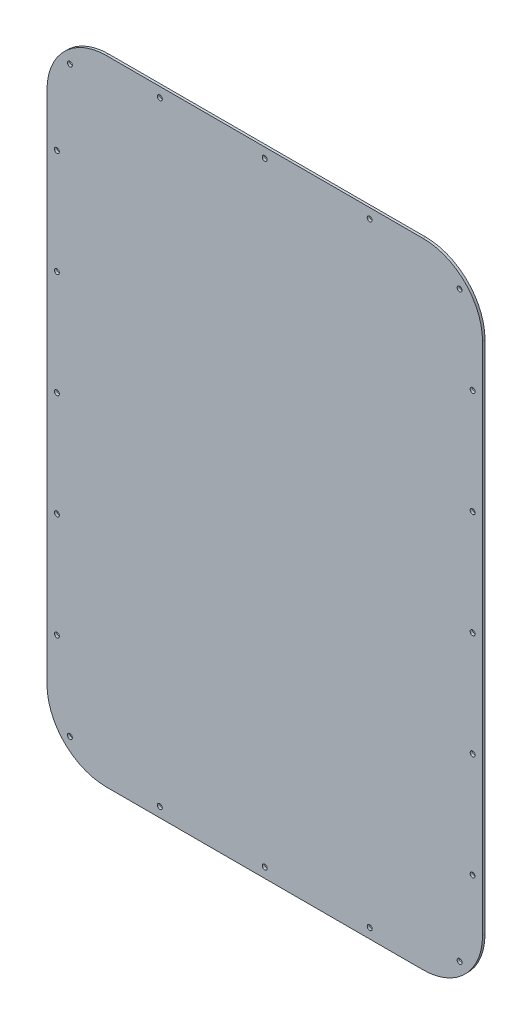
SolidWorks part; units mm, degrees
ref_plane "Front Plane" through (0, 0, 0) normal (0, 0, 1) x (1, 0, 0)
ref_plane "Top Plane" through (0, 0, 0) normal (0, 1, 0) x (1, 0, 0)
ref_plane "Right Plane" through (0, 0, 0) normal (1, 0, 0) x (0, 0, -1)
sketch "Model" plane through (0, 0, 0) normal (0, 0, 1) x (1, 0, 0)
  line L19 (76.2, 1549.5397) -> (76.2, 889.1397)
  line L20 (152.4, 812.9397) -> (558.8, 812.9397)
  line L21 (635, 889.1397) -> (635, 1549.5397)
  line L22 (558.8, 1625.7397) -> (152.4, 1625.7397)
  circle A25 centre (605.6173, 1592.8673) radius 3.175
  circle A26 centre (605.6173, 845.8122) radius 3.175
  circle A27 centre (105.5827, 845.8122) radius 3.175
  circle A28 centre (88.9, 1219.3397) radius 3.175
  circle A29 centre (88.9, 1084.7197) radius 3.175
  circle A30 centre (88.9, 1488.5797) radius 3.175
  circle A31 centre (88.9, 1353.9597) radius 3.175
  circle A32 centre (88.9, 950.0997) radius 3.175
  circle A33 centre (622.3, 1219.3397) radius 3.175
  circle A34 centre (622.3, 950.0997) radius 3.175
  circle A35 centre (622.3, 1084.7197) radius 3.175
  circle A36 centre (622.3, 1488.5797) radius 3.175
  circle A37 centre (622.3, 1353.9597) radius 3.175
  circle A38 centre (355.6, 1613.0397) radius 3.175
  circle A39 centre (220.98, 825.6397) radius 3.175
  circle A40 centre (490.22, 825.6397) radius 3.175
  circle A41 centre (355.6, 825.6397) radius 3.175
  circle A42 centre (105.5827, 1592.8673) radius 3.175
  circle A43 centre (220.98, 1613.0397) radius 3.175
  circle A44 centre (490.22, 1613.0397) radius 3.175
  arc A54 (152.4, 1625.7397) -> (76.2, 1549.5397) centre (152.4, 1549.5397) ccw
  arc A55 (76.2, 889.1397) -> (152.4, 812.9397) centre (152.4, 889.1397) ccw
  arc A56 (558.8, 812.9397) -> (635, 889.1397) centre (558.8, 889.1397) ccw
  arc A57 (635, 1549.5397) -> (558.8, 1625.7397) centre (558.8, 1549.5397) ccw
extrude "Boss-Extrude1" add sketch "Model" along normal blind 3.175
